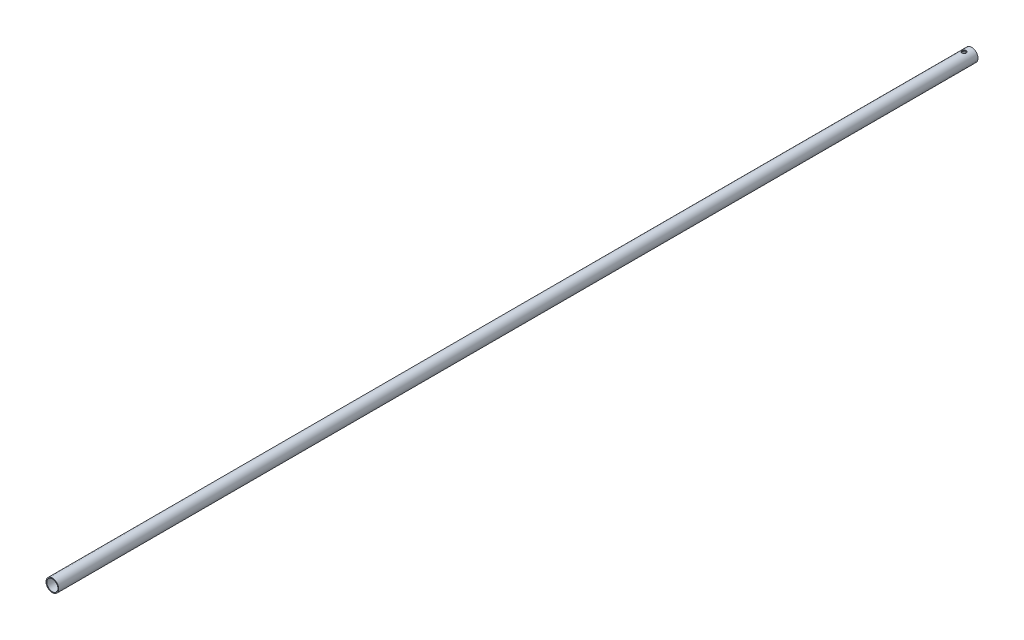
SolidWorks part; units mm, degrees
material "PVC Rigid"
ref_plane "Front Plane" through (0, 0, 0) normal (0, 0, 1) x (1, 0, 0)
ref_plane "Top Plane" through (0, 0, 0) normal (0, 1, 0) x (1, 0, 0)
ref_plane "Right Plane" through (0, 0, 0) normal (1, 0, 0) x (0, 0, -1)
sketch "Sketch1" plane through (0, 0, 0) normal (0, 0, 1) x (1, 0, 0)
  circle A0 centre (0, 0) radius 16.51
  circle A1 centre (0, 0) radius 19.05
  dimension "D1" = 33.02
  dimension "D2" = 38.1
extrude "Boss-Extrude1" add sketch "Sketch1" along normal blind 2743.2
sketch "Sketch2" plane through (0, 0, 0) normal (0, 1, 0) x (1, 0, 0)
  circle A0 centre (0, -22.86) radius 6.35
  dimension "D1" = 12.7
  dimension "D2" = 22.86
extrude "Cut-Extrude1" cut sketch "Sketch2" against normal through all both and the other way through all
